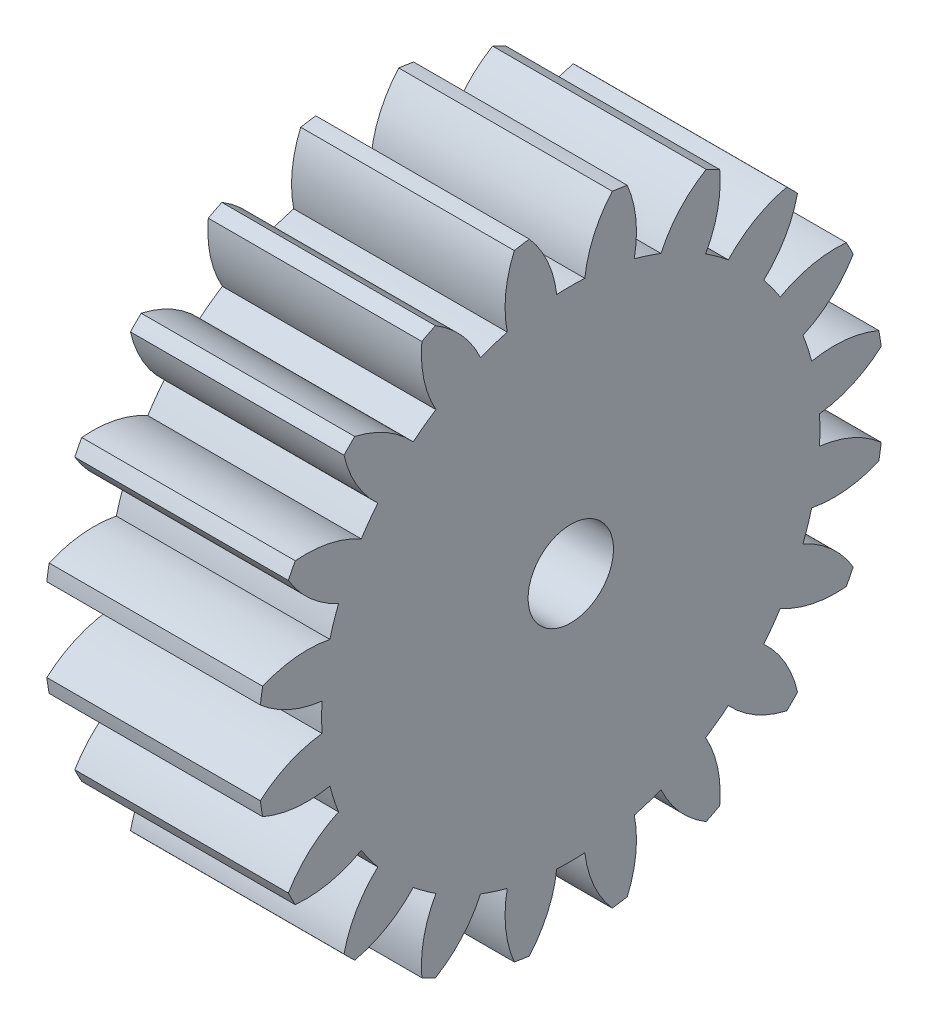
SolidWorks part; units mm, degrees
ref_plane "Plane1" through (0, 0, 0) normal (0, 0, 1) x (1, 0, 0)
ref_plane "Plane2" through (0, 0, 0) normal (0, 1, 0) x (1, 0, 0)
ref_plane "Plane3" through (0, 0, 0) normal (1, 0, 0) x (0, 0, -1)
other "Configuration Table"
sketch "HoldingSke" plane through (0, 0, 0) normal (0, 1, 0) x (1, 0, 0)
  line L0 (0, 0) -> (0.4698, -0.171)
  line L1 (-15, 0) -> (100, 0) construction
  line L2 (0, 0) -> (-2.1039, 2.3779)
  line L3 (0, 0) -> (-11.863, 4.5341)
  line L4 (0, 0) -> (8.1152, 2.9537)
  line L5 (0, 0) -> (-46.8476, -17.4728)
  line L6 (0, 0) -> (-12.4344, -8.3896)
  line L7 (-2.1039, 2.3779) -> (8.6586, 51.2059)
  line L8 (-76.2, 54.61) -> (-75.2, 54.61)
  line L9 (-71.009, 38.7566) -> (-53.1078, 45.2721)
  line L10 (-76.2, 71.12) -> (104.1128, 71.12)
  line L11 (0, 0) -> (-15, 0)
  line L12 (-76.2, 101.6) -> (-76.133, 101.6)
  line L13 (24.9733, 27.94) -> (52.9518, 28.4284)
  line L14 (24.9733, 27.94) -> (24.9743, 27.94)
  line L15 (24.9733, 27.94) -> (100.4006, 29.5858)
  line L16 (-63.627, -2) -> (-12.827, -2)
  circle A0 centre (0, 0) radius 3
  circle A1 centre (0, 0) radius 17.499
  circle A2 centre (0, 0) radius 37.5
  circle A3 centre (0, 0) radius 3
  dimension "MHD" = 34.998
  dimension "Hub_dia" = 75
  dimension "Bore" = 6
  dimension "MBD" = 6
  dimension "Num_teeth" = 20
  dimension "Pitch" = 0.5
  dimension "Overall_len" = 50
  dimension "Show_teeth" = 20
  dimension "Thickness" = 15
  dimension "OAL" = 50.0001
  dimension "T_dim" = 1
  dimension "Ap" = 20
  dimension "H" = 19.05
  dimension "Pitch_radius" = 180.3128
  dimension "Width" = 15
  dimension "Backlash" = 0.067
  dimension "Addendum_fac" = 1
  dimension "Dedendum_fac" = 1.25
  dimension "Clearance_fac" = 0.25
  dimension "Dedendum_add" = 0.001
  dimension "Module" = 2
sketch "BasProSke" plane through (0, 0, 0) normal (0, 1, 0) x (1, 0, 0)
  line L0 (-10, 0) -> (60, 0) construction
  line L1 (0, 0) -> (0, 22)
  line L2 (0, 0) -> (15, 0)
  line L3 (15, 0) -> (15, 22)
  line L4 (15, 22) -> (0, 22)
  dimension "Thickness" = 15
  dimension "Diameter" = 44
revolve "Base-Revolve" add sketch "BasProSke" angle 360 about L0
sketch "TooCutSke" plane through (0, 0, 0) normal (1, 0, 0) x (0, 0, -1)
  line L1 (0, 0) -> (0, 107) construction
  line L2 (0, 0) -> (-1.6864, 19.9288) construction
  line L3 (0, 0) -> (-6.2409, 39.4033) construction
  line L4 (-1.6864, 19.9288) -> (-3.1204, 19.7016) construction
  arc A0 (0.9862, 17.4712) -> (-0.9862, 17.4712) centre (0, 0) ccw
  arc A1 (2.9329, 21.8293) -> (-2.9329, 21.8293) centre (0, 0) ccw
  circle A2 centre (0, 0) radius 20 construction
  circle A3 centre (0, 0) radius 18.7939 construction
  arc A4 (-0.9862, 17.4712) -> (-2.9329, 21.8293) centre (-8.9313, 16.536) ccw
  arc A5 (2.9329, 21.8293) -> (0.9862, 17.4712) centre (8.9313, 16.536) ccw
  dimension "Root_dia" = 34.998
  dimension "Overcut_dia" = 44.0508
  dimension "Pitch_dia" = 40
  dimension "Base_dia" = 37.5877
  dimension "Flank_rad" = 8
  dimension "Half_ang" = 9
  dimension "Half_CT" = 1.4519
extrude "ToothCut" cut sketch "TooCutSke" along normal through all
fillet "Breaks" [suppressed] radius 0.04
fillet "RootFillets" [suppressed] radius 0.501
pattern_circular "TeethCuts" count 20 every 18 about axis through (-10, 0, 0) along (1, 0, 0) of "ToothCut", "RootFillets", "Breaks"
sketch "HubNeaOneSke" plane through (0, 0, 0) normal (-1, 0, 0) x (0, 0, 1)
  circle A0 centre (0, 0) radius 17.499
  dimension "Diameter" = 34.998
extrude "HubNearOne" [suppressed] add sketch "HubNeaOneSke" along normal blind 35.0001
sketch "HubNeaBotSke" plane through (0, 0, 0) normal (-1, 0, 0) x (0, 0, 1)
  circle A0 centre (0, 0) radius 17.499
  dimension "Diameter" = 34.998
extrude "HubNearBoth" [suppressed] add sketch "HubNeaBotSke" along normal blind 17.5
ref_plane "FarPln" through (15, 0, 0) normal (1, 0, 0) x (0, 0, -1)
sketch "HubFarSke" plane through (15, 0, 0) normal (1, 0, 0) x (0, 0, -1)
  circle A0 centre (0, 0) radius 17.499
  dimension "Diameter" = 34.998
extrude "HubFar" [suppressed] add sketch "HubFarSke" along normal blind 17.5
sketch "BorSke" plane through (0, 0, 0) normal (1, 0, 0) x (0, 0, -1)
  circle A0 centre (0, 0) radius 3
  dimension "Diameter" = 6
extrude "Bore" cut sketch "BorSke" along normal mid plane 100.0001
sketch "KeySke" plane through (0, 0, 0) normal (1, 0, 0) x (0, 0, -1)
  line L0 (-1, 0) -> (-1, 4)
  line L1 (-1, 4) -> (1, 4)
  line L2 (1, 4) -> (1, 0)
  line L3 (0, 0) -> (0, 34) construction
  line L4 (-1, 0) -> (1, 0)
  dimension "Offset" = 4
  dimension "Width" = 2
extrude "Keyway" [suppressed] cut sketch "KeySke" along normal mid plane 100.0001
pattern_circular "Keyway2" [suppressed] count 2 every 90 about axis through (-10, 0, 0) along (1, 0, 0)
equation "' \"Module@HoldingSke\" = 6.35"
equation "' \"Num_teeth@HoldingSke\" = 12"
equation "' \"Ap@HoldingSke\" =  20"
equation "' \"Ap@HoldingSke\" = 20"
equation "' \"Width@HoldingSke\" = 0.5 * 25.4"
equation "' \"Hub_dia@HoldingSke\"= 1 * 25.4"
equation "' \"Hub_dia@HoldingSke\" = 1 * 25.4"
equation "' \"Overall_len@HoldingSke\" = 1.0 * 25.4"
equation "' \"Bore@HoldingSke\" = 0.75 * 25.4"
equation "' \"T_dim@HoldingSke\" = 0.1 * 25.4"
equation "' \"Width@KeySke\" = 0.25 * 25.4"
equation "' \"Show_teeth@HoldingSke\" = 13"
equation "' \"Backlash@HoldingSke\" = 0.009 * 25.4"
equation "' \"Addendum_fac@HoldingSke\" = 1.0"
equation "' \"Dedendum_fac@HoldingSke\" = 1.25"
equation "' \"Dedendum_add@HoldingSke\" = 0.00005 * 25.4"
equation "' \"Clearance_fac@HoldingSke\" = 0.25"
equation "\"Pitch@HoldingSke\" = 1 / \"Module@HoldingSke\""
equation "\"Overcut_dia@TooCutSke\" = (\"Num_teeth@HoldingSke\" + 2 * \"Addendum_fac@HoldingSke\") / \"Pitch@HoldingSke\" + 0.002 * 25.4"
equation "\"Pitch_dia@TooCutSke\" = \"Num_teeth@HoldingSke\" / \"Pitch@HoldingSke\""
equation "\"Base_dia@TooCutSke\" = \"Num_teeth@HoldingSke\" / \"Pitch@HoldingSke\" * cos((\"Ap@HoldingSke\"  * 3.14159265 / 180))"
equation "\"Root_dia@TooCutSke\" = (\"Num_teeth@HoldingSke\" + 2) / \"Pitch@HoldingSke\" - 2 * (\"Addendum_fac@HoldingSke\" + \"Dedendum_fac@HoldingSke\") / \"Pitch@HoldingSke\" - \"Dedendum_add@HoldingSke\" * 2"
equation "\"Half_ang@TooCutSke\" = 180 / \"Num_teeth@HoldingSke\""
equation "\"Half_CT@TooCutSke\" = \"Num_teeth@HoldingSke\" / \"Pitch@HoldingSke\" * sin((3.14159265 / 2 / \"Num_teeth@HoldingSke\")) / 2 - 7 * \"Backlash@HoldingSke\" / 4"
equation "\"Flank_rad@TooCutSke\" = \"Num_teeth@HoldingSke\" / \"Pitch@HoldingSke\" / 5"
equation "\"Radius@RootFillets\" = \"Clearance_fac@HoldingSke\" / \"Pitch@HoldingSke\" + \"Dedendum_add@HoldingSke\""
equation "\"Break_rad@Breaks\" = 0.02 / \"Pitch@HoldingSke\""
equation "\"Thickness@HoldingSke\" = \"Width@HoldingSke\""
equation "\"OAL@HoldingSke\" = \"Thickness@HoldingSke\""
equation "\"MHD@HoldingSke\" = (\"Num_teeth@HoldingSke\" + 2) / \"Pitch@HoldingSke\" - 2 * (\"Addendum_fac@HoldingSke\" + \"Dedendum_fac@HoldingSke\")  / \"Pitch@HoldingSke\" - \"Dedendum_add@HoldingSke\" * 2"
equation "\"MBD@HoldingSke\" = (\"Num_teeth@HoldingSke\" + 2) / \"Pitch@HoldingSke\" - 2 * (\"Addendum_fac@HoldingSke\" + \"Dedendum_fac@HoldingSke\")  / \"Pitch@HoldingSke\" - \"Dedendum_add@HoldingSke\" * 2 - 0.002 * 25.4"
equation "\"MHD@HoldingSke\" = ((sgn( \"MHD@HoldingSke\" - \"Hub_dia@HoldingSke\" )-1)*( \"MHD@HoldingSke\" - \"Hub_dia@HoldingSke\" ))/-2+ \"Hub_dia@HoldingSke\""
equation "\"MBD@HoldingSke\" = ((sgn( \"MBD@HoldingSke\" - \"Bore@HoldingSke\" )-1)*( \"MBD@HoldingSke\" - \"Bore@HoldingSke\" ))/-2+ \"Bore@HoldingSke\""
equation "\"OAL@HoldingSke\" = ((sgn( \"OAL@HoldingSke\" - \"Overall_len@HoldingSke\" )+1)*( \"OAL@HoldingSke\" - \"Overall_len@HoldingSke\" ))/2 + \"Overall_len@HoldingSke\" + 0.000002 * 25.4"
equation "\"Num_teeth@TeethCuts\" = int( \"Show_teeth@HoldingSke\" ) + 1"
equation "\"Num_teeth@TeethCuts\" = ((sgn( \"Num_teeth@TeethCuts\" - \"Num_teeth@HoldingSke\" )-1)*( \"Num_teeth@TeethCuts\" - \"Num_teeth@HoldingSke\" ))/-2+ \"Num_teeth@HoldingSke\""
equation "\"Num_teeth@TeethCuts\" = ((sgn( \"Num_teeth@TeethCuts\" - 2.0)+1)*( \"Num_teeth@TeethCuts\" - 2.0))/2 +2.0"
equation "\"Angle@TeethCuts\" = 360.0 / \"Num_teeth@HoldingSke\""
equation "\"Diameter@BasProSke\" = (\"Num_teeth@HoldingSke\" + 2 * \"Addendum_fac@HoldingSke\") / \"Pitch@HoldingSke\""
equation "\"Thickness@BasProSke\"  = \"Thickness@HoldingSke\""
equation "' \"Fillet_rad@BasProSke\" =  \"Thickness@HoldingSke\" * 0.05"
equation "' \"Fillet_rad@BasProSke\" = \"Thickness@HoldingSke\" * 0.05"
equation "\"MHD@HoldingSke\" = ((sgn( \"MHD@HoldingSke\" - \"Root_dia@TooCutSke\" )-1)*( \"MHD@HoldingSke\" - \"Root_dia@TooCutSke\" ))/-2+ \"Root_dia@TooCutSke\""
equation "\"Diameter@HubNeaOneSke\" = \"MHD@HoldingSke\""
equation "\"Length@HubNearOne\" = \"OAL@HoldingSke\" - \"Thickness@BasProSke\""
equation "\"Diameter@HubNeaBotSke\" = \"MHD@HoldingSke\""
equation "\"Length@HubNearBoth\" = ( \"OAL@HoldingSke\" - \"Thickness@BasProSke\" ) / 2.0"
equation "\"Thickness@FarPln\" = \"Thickness@BasProSke\""
equation "\"Diameter@HubFarSke\" = \"MHD@HoldingSke\""
equation "\"Length@HubFar\" = ( \"OAL@HoldingSke\" - \"Thickness@BasProSke\" ) / 2.0"
equation "\"Diameter@BorSke\" = \"MBD@HoldingSke\""
equation "\"D1@Bore\" = \"OAL@HoldingSke\" * 2.0"
equation "\"D1@Keyway\" = \"OAL@HoldingSke\" * 2.0"
equation "\"Offset@KeySke\" = \"T_dim@HoldingSke\" + \"MBD@HoldingSke\" / 2.0"
